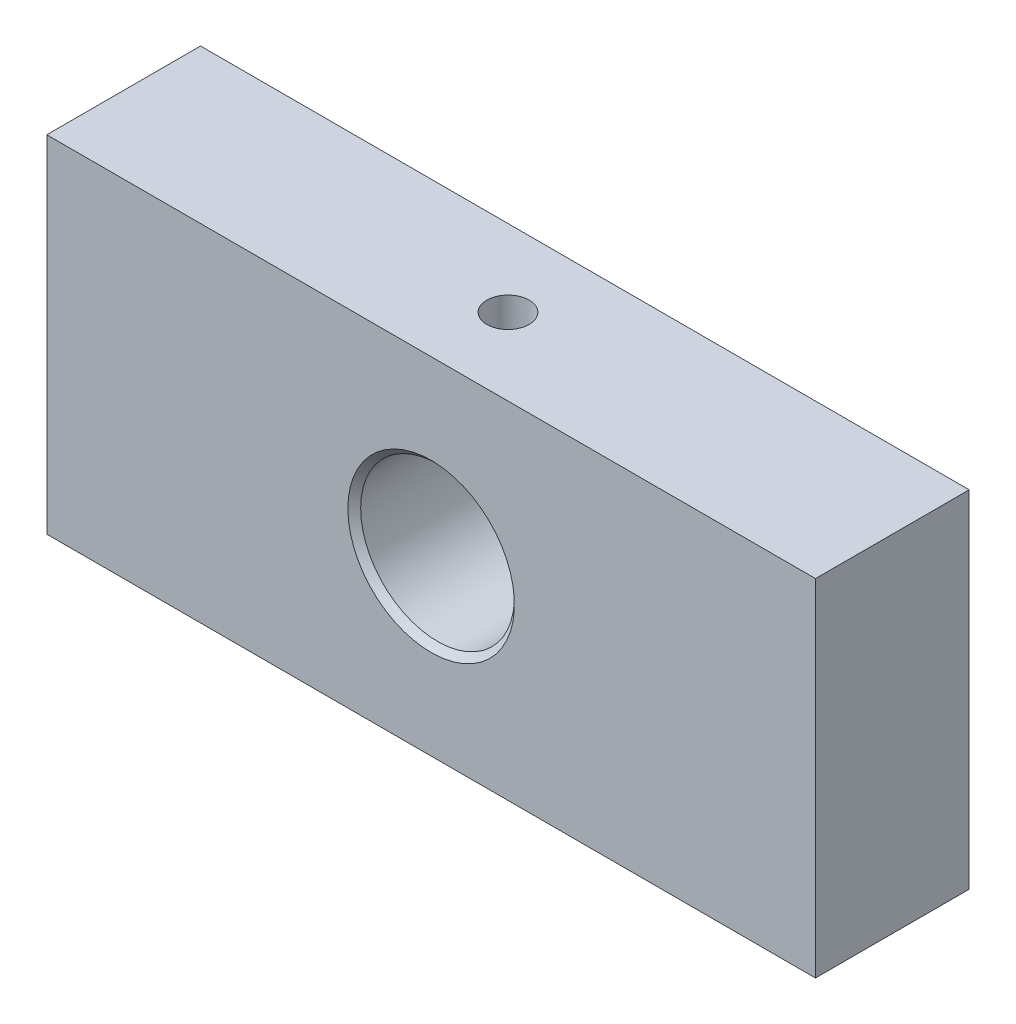
SolidWorks part; units mm, degrees
ref_plane "Front Plane" through (0, 0, 0) normal (0, 0, 1) x (1, 0, 0)
ref_plane "Top Plane" through (0, 0, 0) normal (0, 1, 0) x (1, 0, 0)
ref_plane "Right Plane" through (0, 0, 0) normal (1, 0, 0) x (0, 0, -1)
sketch "Sketch2" plane through (0, 0, 0) normal (0, 0, 1) x (1, 0, 0)
  line L1 (0, 0) -> (60, 0)
  line L2 (0, 0) -> (0, 27)
  line L3 (0, 27) -> (60, 27)
  line L4 (60, 0) -> (60, 27)
  dimension "D1" = 60
  dimension "D2" = 27
extrude "Boss-Extrude1" add sketch "Sketch2" along normal blind 12
sketch "Sketch3" plane through (0, 0, 12) normal (0, 0, 1) x (1, 0, 0)
  line L0 (0, 13.5) -> (60, 13.5) construction
  line L1 (0, 27) -> (0, 0) construction
  line L2 (60, 0) -> (60, 27) construction
hole_wizard "Ø12.0mm Clearance Dowel Hole1" positions "Sketch5" profile "Sketch6" hole size "Ø12.0" standard "DIN"
sketch "Sketch5" plane through (0, 0, 12) normal (0, 0, 1) x (1, 0, 0)
  line L0 (0, 13.5) -> (60, 13.5) construction
  point P0 (30, 13.5)
sketch "Sketch6" plane through (30, 13.5, 12) normal (1, 0, 0) x (0, -1, 0)
  line L0 (0, 0) -> (0, 16.0052)
  line L1 (0, 16.0052) -> (6, 12.4)
  line L2 (6, 12.4) -> (6, 0)
  line L5 (6, 0) -> (0, 0)
  line L10 (0, 16.0052) -> (-6, 12.4) construction
  line L11 (0, -6.35) -> (0, 107.95) construction
  dimension "Hole Dia." = 12
  dimension "Hole Depth" = 12.4
  dimension "Drill Angle" = 118
sketch3d "3DSketch1"
  line L0 (0, 27, 6) -> (60, 27, 6) construction
  line L1 (0, 27, 12) -> (0, 27, 0) construction
  line L2 (60, 27, 12) -> (60, 27, 0) construction
hole_wizard "M4 Tapped Hole1" positions "Sketch10" profile "Sketch11" tap size "M4" standard "DIN"
sketch "Sketch10" plane through (0, 27, 0) normal (0, 1, 0) x (1, 0, 0)
  line L0 (0, -6) -> (60, -6) construction
  point P0 (30, -6)
sketch "Sketch11" plane through (30, 27, 6) normal (1, 0, 0) x (0, 0, 1)
  line L0 (0, 0) -> (0, 11.0914)
  line L1 (0, 11.0914) -> (1.65, 10.1)
  line L2 (1.65, 10.1) -> (1.65, 0)
  line L5 (1.65, 0) -> (0, 0)
  line L10 (0, 11.0914) -> (-1.65, 10.1) construction
  line L11 (0, -6.35) -> (0, 107.95) construction
  dimension "Tap Drill Dia." = 3.3
  dimension "Tap Drill Depth" = 10.1
  dimension "Drill Angle" = 118
cosmetic thread "Hole Thread1" parameters "D1"=7.7313, "D2"=4
chamfer "Chamfer1" distance 0.5 angle 45 1 edges at (36, 13.5, 12)
sketch "Sketch12" plane through (0, 0, 0) normal (0, -1, 0) x (1, 0, 0)
  line L0 (0, 6) -> (16, 6) construction
  line L1 (0, 12) -> (0, 0) construction
  line L2 (8, 6) -> (8, 2.9609) construction
  line L7 (44, 6) -> (60, 6) construction
  line L8 (52, 6) -> (52, 2.9609) construction
  dimension "D1" = 2
hole_wizard "Ø5.0mm Clearance Dowel Hole3" positions "3DSketch6" profile "Sketch21" hole size "Ø5.0" standard "DIN"
sketch3d "3DSketch6"
  point P0 (8, 0, 6)
sketch "Sketch21" plane through (8, 0, 6) normal (1, 0, 0) x (0, 0, -1)
  line L0 (0, 0) -> (0, 11.5022)
  line L1 (0, 11.5022) -> (2.5, 10)
  line L2 (2.5, 10) -> (2.5, 0)
  line L5 (2.5, 0) -> (0, 0)
  line L10 (0, 11.5022) -> (-2.5, 10) construction
  line L11 (0, -6.35) -> (0, 107.95) construction
  dimension "Hole Dia." = 5
  dimension "Hole Depth" = 10
  dimension "Drill Angle" = 118
hole_wizard "M5 Tapped Hole3" positions "3DSketch7" profile "Sketch22" tap size "M5" standard "DIN"
sketch3d "3DSketch7"
  point P0 (16, 0, 6)
sketch "Sketch22" plane through (16, 0, 6) normal (1, 0, 0) x (0, 0, -1)
  line L0 (0, 0) -> (0, 11.2618)
  line L1 (0, 11.2618) -> (2.1, 10)
  line L2 (2.1, 10) -> (2.1, 0)
  line L5 (2.1, 0) -> (0, 0)
  line L10 (0, 11.2618) -> (-2.1, 10) construction
  line L11 (0, -6.35) -> (0, 107.95) construction
  dimension "Tap Drill Dia." = 4.2
  dimension "Tap Drill Depth" = 10
  dimension "Drill Angle" = 118
cosmetic thread "Hole Thread4" parameters "D1"=10, "D2"=5
hole_wizard "M5 Tapped Hole4" positions "3DSketch8" profile "Sketch24" tap size "M5" standard "DIN"
sketch3d "3DSketch8"
  point P0 (44, 0, 6)
sketch "Sketch24" plane through (44, 0, 6) normal (1, 0, 0) x (0, 0, -1)
  line L0 (0, 0) -> (0, 11.2618)
  line L1 (0, 11.2618) -> (2.1, 10)
  line L2 (2.1, 10) -> (2.1, 0)
  line L5 (2.1, 0) -> (0, 0)
  line L10 (0, 11.2618) -> (-2.1, 10) construction
  line L11 (0, -6.35) -> (0, 107.95) construction
  dimension "Tap Drill Dia." = 4.2
  dimension "Tap Drill Depth" = 10
  dimension "Drill Angle" = 118
cosmetic thread "Hole Thread5" parameters "D1"=10, "D2"=5
hole_wizard "Ø5.0mm Clearance Dowel Hole4" positions "3DSketch9" profile "Sketch25" hole size "Ø5.0" standard "DIN"
sketch3d "3DSketch9"
  point P0 (52, 0, 6)
sketch "Sketch25" plane through (52, 0, 6) normal (1, 0, 0) x (0, 0, -1)
  line L0 (0, 0) -> (0, 13.9022)
  line L1 (0, 13.9022) -> (2.5, 12.4)
  line L2 (2.5, 12.4) -> (2.5, 0)
  line L5 (2.5, 0) -> (0, 0)
  line L10 (0, 13.9022) -> (-2.5, 12.4) construction
  line L11 (0, -6.35) -> (0, 107.95) construction
  dimension "Hole Dia." = 5
  dimension "Hole Depth" = 12.4
  dimension "Drill Angle" = 118
